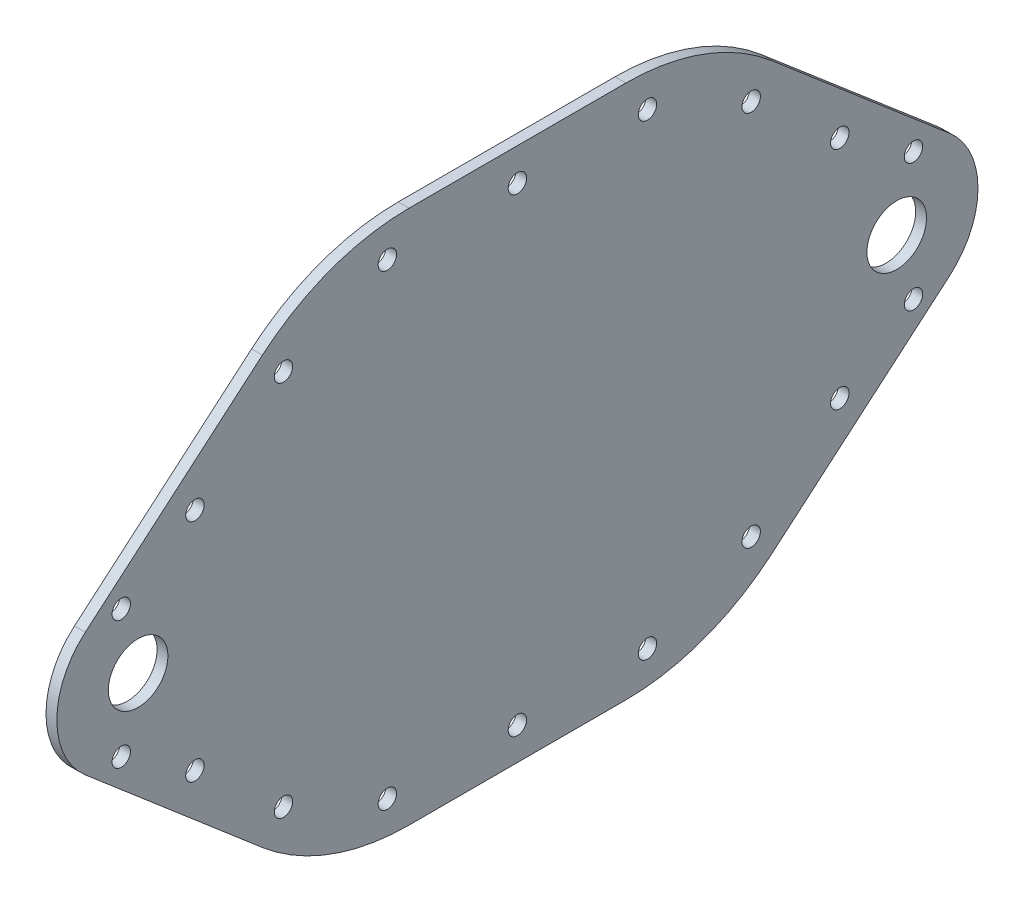
SolidWorks part; units mm, degrees
ref_plane "Front Plane" through (0, 0, 0) normal (0, 0, 1) x (1, 0, 0)
ref_plane "Top Plane" through (0, 0, 0) normal (0, 1, 0) x (1, 0, 0)
ref_plane "Right Plane" through (0, 0, 0) normal (1, 0, 0) x (0, 0, -1)
sketch "Sketch1" plane through (0, 0, 0) normal (1, 0, 0) x (0, 0, -1)
  line L0 (-25.4, 62.611) -> (25.4, 62.611)
  line L1 (-107.95, -62.611) -> (107.95, -62.611) construction
  line L2 (-107.95, -62.611) -> (-107.95, 62.611) construction
  line L3 (-107.95, 62.611) -> (107.95, 62.611) construction
  line L4 (107.95, -62.611) -> (107.95, 62.611) construction
  line L5 (-107.95, -62.611) -> (107.95, 62.611) construction
  line L6 (-107.95, 62.611) -> (107.95, -62.611) construction
  line L7 (-101.281, 14.478) -> (-59.7774, 49.9703)
  line L8 (-101.281, -14.478) -> (-59.7774, -49.9703)
  line L9 (-25.4, -62.611) -> (25.4, -62.611)
  line L10 (101.2694, 14.4879) -> (59.7372, 49.9468)
  line L11 (101.2694, -14.488) -> (59.7372, -49.9468)
  circle A0 centre (88.9, 0) radius 19.05
  circle A1 centre (-88.9, 0) radius 19.05
  arc A2 (-25.4, 62.611) -> (-59.7774, 49.9703) centre (-25.4, 9.5445) ccw
  arc A3 (-25.4, -62.611) -> (-59.7774, -49.9703) centre (-25.4, -9.5445) cw
  arc A4 (25.4, 62.611) -> (59.7372, 49.9468) centre (25.4, 9.7285) cw
  arc A5 (25.4, -62.611) -> (59.7372, -49.9468) centre (25.4, -9.7285) ccw
  point P0 (0, 0)
  point P13 (0, 62.611)
  point P21 (0, -62.611)
  dimension "D3" = 38.1
  dimension "D1" = 125.222
  dimension "D2" = 215.9
  dimension "D4" = 50.8
  dimension "D5" = 14.478
  dimension "D6" = 54.61
  dimension "D7" = 88.9
  dimension "D8" = 88.9
  dimension "D9" = 14.478
  dimension "D10" = 54.61
extrude "Boss-Extrude1" add sketch "Sketch1" along normal blind 2.54 contours L9 A5 L11 A0 L10 A4 L0 A2 L7 A1 L8 A3 | A0 | A1
sketch "Sketch4" plane through (2.54, 0, 0) normal (1, 0, 0) x (0, 0, -1)
  line L0 (-131.1141, 0) -> (130.289, 0) construction
  line L12 (-25.4, -54.991) -> (25.4, -54.991)
  line L13 (54.7895, -44.1517) -> (96.3216, -8.6928)
  line L14 (96.3216, 8.6928) -> (54.7895, 44.1517)
  line L15 (25.4, 54.991) -> (-25.4, 54.991)
  line L16 (-54.8333, 44.172) -> (-96.3286, 8.6868)
  line L17 (-96.3286, -8.6868) -> (-54.8333, -44.172)
  line L18 (-25.4, -54.991) -> (25.4, -54.991)
  line L19 (54.7895, -44.1517) -> (96.3216, -8.6928)
  line L20 (96.3216, 8.6928) -> (54.7895, 44.1517)
  line L21 (25.4, 54.991) -> (-25.4, 54.991)
  line L22 (-54.8333, 44.172) -> (-96.3286, 8.6868)
  line L23 (-96.3286, -8.6868) -> (-54.8333, -44.172)
  circle A0 centre (-30.48, 54.7062) radius 2.159
  circle A1 centre (-54.8333, 44.172) radius 2.159
  circle A2 centre (54.7895, 44.1517) radius 2.159
  circle A3 centre (30.4787, 54.7052) radius 2.159
  circle A4 centre (-75.581, 26.4294) radius 2.159
  circle A5 centre (75.5556, 26.4222) radius 2.159
  circle A8 centre (0, 54.991) radius 2.159
  circle A11 centre (-92.853, 14.9994) radius 2.159
  arc A12 (25.4, -54.991) -> (54.7895, -44.1517) centre (25.4, -9.7285) ccw
  arc A13 (96.3216, -8.6928) -> (96.3216, 8.6928) centre (88.9, 0) ccw
  arc A14 (54.7895, 44.1517) -> (25.4, 54.991) centre (25.4, 9.7285) ccw
  arc A15 (-25.4, 54.991) -> (-54.8333, 44.172) centre (-25.4, 9.5445) ccw
  arc A16 (-96.3286, 8.6868) -> (-96.3286, -8.6868) centre (-88.9, 0) ccw
  arc A17 (-54.8333, -44.172) -> (-25.4, -54.991) centre (-25.4, -9.5445) ccw
  arc A18 (25.4, -54.991) -> (54.7895, -44.1517) centre (25.4, -9.7285) ccw
  arc A19 (96.3216, -8.6928) -> (96.3216, 8.6928) centre (88.9, 0) ccw
  arc A20 (54.7895, 44.1517) -> (25.4, 54.991) centre (25.4, 9.7285) ccw
  arc A21 (-25.4, 54.991) -> (-54.8333, 44.172) centre (-25.4, 9.5445) ccw
  arc A22 (-96.3286, 8.6868) -> (-96.3286, -8.6868) centre (-88.9, 0) ccw
  arc A23 (-54.8333, -44.172) -> (-25.4, -54.991) centre (-25.4, -9.5445) ccw
  circle A24 centre (92.8276, 14.9922) radius 2.159
  circle A25 centre (92.8276, -14.9922) radius 2.159
  circle A26 centre (75.5556, -26.4222) radius 2.159
  circle A27 centre (54.7895, -44.1517) radius 2.159
  circle A28 centre (30.4787, -54.7052) radius 2.159
  circle A29 centre (0, -54.991) radius 2.159
  circle A30 centre (-30.48, -54.7062) radius 2.159
  circle A31 centre (-54.8333, -44.172) radius 2.159
  circle A32 centre (-75.581, -26.4294) radius 2.159
  circle A33 centre (-92.853, -14.9994) radius 2.159
  dimension "D2" = 4.318
  dimension "D5" = 4.318
  dimension "D6" = 4.318
  dimension "D9" = 4.318
  dimension "D3" = 30.48
  dimension "D4" = 30.48
  dimension "D7" = 11.43
  dimension "D8" = 17.272
  dimension "D10" = 17.272
  dimension "D11" = 11.43
  dimension "D1" = 7.62
extrude "Cut-Extrude3" cut sketch "Sketch4" against normal through all both and the other way through all contours A1 | A0 | A8 | A3 | A2 | A5 | A24 | A25 | A26 | A27 | A28 | A29 | A30 | A31 | A32 | A4 | A33 | A11
sketch "Sketch5" plane through (2.54, 0, 0) normal (1, 0, 0) x (0, 0, -1)
  circle A0 centre (-88.9, 0) radius 6.985
  circle A1 centre (88.9, 0) radius 6.985
  dimension "D1" = 13.97
  dimension "D2" = 13.97
extrude "Cut-Extrude4" cut sketch "Sketch5" against normal blind 6.35
